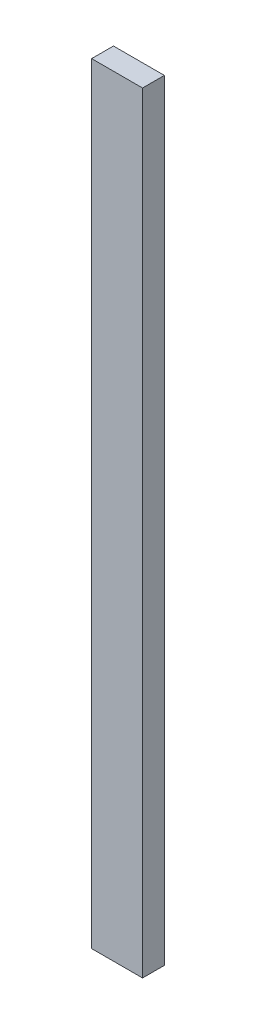
SolidWorks part; units mm, degrees
ref_plane "Front Plane" through (0, 0, 0) normal (0, 0, 1) x (1, 0, 0)
ref_plane "Top Plane" through (0, 0, 0) normal (0, 1, 0) x (1, 0, 0)
ref_plane "Right Plane" through (0, 0, 0) normal (1, 0, 0) x (0, 0, -1)
sketch "Sketch1" plane through (0, 0, 0) normal (0, 1, 0) x (1, 0, 0)
  line L1 (-44.45, -19.05) -> (44.45, -19.05)
  line L2 (-44.45, -19.05) -> (-44.45, 19.05)
  line L3 (-44.45, 19.05) -> (44.45, 19.05)
  line L4 (44.45, -19.05) -> (44.45, 19.05)
  line L5 (-44.45, -19.05) -> (44.45, 19.05) construction
  line L6 (-44.45, 19.05) -> (44.45, -19.05) construction
  point P0 (0, 0)
  dimension "D1" = 88.9
  dimension "D2" = 38.1
extrude "Boss-Extrude1" add sketch "Sketch1" along normal blind 1346.2
